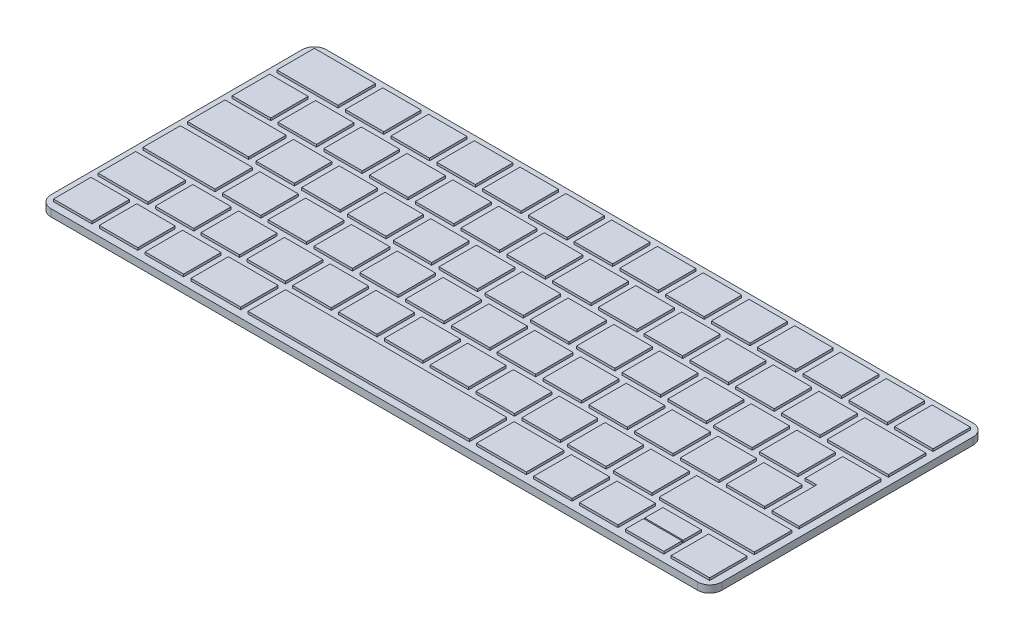
SolidWorks part; units mm, degrees
ref_plane "Front Plane" through (0, 0, 0) normal (0, 0, 1) x (1, 0, 0)
ref_plane "Top Plane" through (0, 0, 0) normal (0, 1, 0) x (1, 0, 0)
ref_plane "Right Plane" through (0, 0, 0) normal (1, 0, 0) x (0, 0, -1)
sketch "Sketch2" plane through (0, 0, 0) normal (1, 0, 0) x (0, 0, -1)
  line L0 (0, 0) -> (-114.5, 0)
  line L1 (-114.5, 0) -> (-114.5, 3)
  line L2 (-114.5, 3) -> (0, 3)
  line L3 (0, 3) -> (0, 0)
  dimension "D2" = 3
  dimension "D3" = 114.5
extrude "Body" add sketch "Sketch2" along normal mid plane 279
sketch "Sketch3" plane through (0, 3, 0) normal (0, 1, 0) x (1, 0, 0)
  line L0 (-139.5, 0) -> (-139.5, -114.5) construction
  line L1 (-136.4455, -111.5) -> (-120.4455, -111.5)
  line L2 (-136.4455, -111.5) -> (-136.4455, -95.9167)
  line L3 (-136.4455, -95.9167) -> (-120.4455, -95.9167)
  line L4 (-120.4455, -111.5) -> (-120.4455, -95.9167)
  line L5 (139.5, -114.5) -> (-139.5, -114.5) construction
  line L6 (-136.4455, -95.9167) -> (-139.5, -95.9167) construction
  line L7 (-117.3909, -111.5) -> (-101.3909, -111.5)
  line L8 (-117.3909, -111.5) -> (-117.3909, -95.9167)
  line L9 (-117.3909, -95.9167) -> (-101.3909, -95.9167)
  line L10 (-101.3909, -111.5) -> (-101.3909, -95.9167)
  line L11 (-98.3364, -111.5) -> (-82.3364, -111.5)
  line L12 (-98.3364, -111.5) -> (-98.3364, -95.9167)
  line L13 (-98.3364, -95.9167) -> (-82.3364, -95.9167)
  line L14 (-82.3364, -111.5) -> (-82.3364, -95.9167)
  line L15 (-79.2818, -111.5) -> (-58.5818, -111.5)
  line L16 (-79.2818, -111.5) -> (-79.2818, -95.9167)
  line L17 (-79.2818, -95.9167) -> (-58.5818, -95.9167)
  line L18 (-58.5818, -111.5) -> (-58.5818, -95.9167)
  line L19 (-55.5273, -111.5) -> (36.4727, -111.5)
  line L20 (-55.5273, -111.5) -> (-55.5273, -95.9167)
  line L21 (-55.5273, -95.9167) -> (36.4727, -95.9167)
  line L22 (36.4727, -111.5) -> (36.4727, -95.9167)
  line L23 (39.5273, -111.5) -> (60.2273, -111.5)
  line L24 (39.5273, -111.5) -> (39.5273, -95.9167)
  line L25 (39.5273, -95.9167) -> (60.2273, -95.9167)
  line L26 (60.2273, -111.5) -> (60.2273, -95.9167)
  line L27 (63.2818, -111.5) -> (79.2818, -111.5)
  line L28 (63.2818, -111.5) -> (63.2818, -95.9167)
  line L29 (63.2818, -95.9167) -> (79.2818, -95.9167)
  line L30 (79.2818, -111.5) -> (79.2818, -95.9167)
  line L31 (82.3364, -111.5) -> (98.3364, -111.5)
  line L32 (82.3364, -111.5) -> (82.3364, -95.9167)
  line L33 (82.3364, -95.9167) -> (98.3364, -95.9167)
  line L34 (98.3364, -111.5) -> (98.3364, -95.9167)
  line L35 (101.3909, -111.5) -> (117.3909, -111.5)
  line L36 (101.3909, -111.5) -> (101.3909, -95.9167)
  line L37 (101.3909, -95.9167) -> (117.3909, -95.9167)
  line L38 (117.3909, -111.5) -> (117.3909, -95.9167)
  line L39 (120.4455, -111.5) -> (136.4455, -111.5)
  line L40 (120.4455, -111.5) -> (120.4455, -95.9167)
  line L41 (120.4455, -95.9167) -> (136.4455, -95.9167)
  line L42 (136.4455, -111.5) -> (136.4455, -95.9167)
  line L43 (-120.4455, -95.9167) -> (-117.3909, -95.9167) construction
  line L44 (-101.3909, -95.9167) -> (-98.3364, -95.9167) construction
  line L45 (-82.3364, -95.9167) -> (-79.2818, -95.9167) construction
  line L46 (-58.5818, -95.9167) -> (-55.5273, -95.9167) construction
  line L47 (36.4727, -95.9167) -> (39.5273, -95.9167) construction
  line L48 (60.2273, -95.9167) -> (63.2818, -95.9167) construction
  line L49 (79.2818, -95.9167) -> (82.3364, -95.9167) construction
  line L50 (136.4455, -95.9167) -> (139.5, -95.9167) construction
  line L51 (98.3364, -95.9167) -> (101.3909, -95.9167) construction
  line L52 (117.3909, -95.9167) -> (120.4455, -95.9167) construction
  line L53 (139.5, 0) -> (139.5, -114.5) construction
  line L54 (-115.7455, -77.3333) -> (-112.6909, -77.3333) construction
  line L55 (-136.4455, -92.9167) -> (-115.7455, -92.9167)
  line L56 (-136.4455, -92.9167) -> (-136.4455, -77.3333)
  line L57 (-136.4455, -77.3333) -> (-115.7455, -77.3333)
  line L58 (-115.7455, -92.9167) -> (-115.7455, -77.3333)
  line L59 (-112.6909, -92.9167) -> (-96.6909, -92.9167)
  line L60 (-112.6909, -92.9167) -> (-112.6909, -77.3333)
  line L61 (-112.6909, -77.3333) -> (-96.6909, -77.3333)
  line L62 (-96.6909, -92.9167) -> (-96.6909, -77.3333)
  line L63 (-93.6364, -92.9167) -> (-77.6364, -92.9167)
  line L64 (-93.6364, -92.9167) -> (-93.6364, -77.3333)
  line L65 (-93.6364, -77.3333) -> (-77.6364, -77.3333)
  line L66 (-77.6364, -92.9167) -> (-77.6364, -77.3333)
  line L67 (-74.5818, -92.9167) -> (-58.5818, -92.9167)
  line L68 (-74.5818, -92.9167) -> (-74.5818, -77.3333)
  line L69 (-74.5818, -77.3333) -> (-58.5818, -77.3333)
  line L70 (-58.5818, -92.9167) -> (-58.5818, -77.3333)
  line L71 (-55.5273, -92.9167) -> (-39.5273, -92.9167)
  line L72 (-55.5273, -92.9167) -> (-55.5273, -77.3333)
  line L73 (-55.5273, -77.3333) -> (-39.5273, -77.3333)
  line L74 (-39.5273, -92.9167) -> (-39.5273, -77.3333)
  line L75 (-36.4727, -92.9167) -> (-20.4727, -92.9167)
  line L76 (-36.4727, -92.9167) -> (-36.4727, -77.3333)
  line L77 (-36.4727, -77.3333) -> (-20.4727, -77.3333)
  line L78 (-20.4727, -92.9167) -> (-20.4727, -77.3333)
  line L79 (-17.4182, -92.9167) -> (-1.4182, -92.9167)
  line L80 (-17.4182, -92.9167) -> (-17.4182, -77.3333)
  line L81 (-17.4182, -77.3333) -> (-1.4182, -77.3333)
  line L82 (-1.4182, -92.9167) -> (-1.4182, -77.3333)
  line L83 (1.6364, -92.9167) -> (17.6364, -92.9167)
  line L84 (1.6364, -92.9167) -> (1.6364, -77.3333)
  line L85 (1.6364, -77.3333) -> (17.6364, -77.3333)
  line L86 (17.6364, -92.9167) -> (17.6364, -77.3333)
  line L87 (20.6909, -92.9167) -> (36.6909, -92.9167)
  line L88 (20.6909, -92.9167) -> (20.6909, -77.3333)
  line L89 (20.6909, -77.3333) -> (36.6909, -77.3333)
  line L90 (36.6909, -92.9167) -> (36.6909, -77.3333)
  line L91 (39.7455, -92.9167) -> (55.7455, -92.9167)
  line L92 (39.7455, -92.9167) -> (39.7455, -77.3333)
  line L93 (39.7455, -77.3333) -> (55.7455, -77.3333)
  line L94 (55.7455, -92.9167) -> (55.7455, -77.3333)
  line L95 (58.8, -92.9167) -> (74.8, -92.9167)
  line L96 (58.8, -92.9167) -> (58.8, -77.3333)
  line L97 (58.8, -77.3333) -> (74.8, -77.3333)
  line L98 (74.8, -92.9167) -> (74.8, -77.3333)
  line L99 (77.8545, -92.9167) -> (93.8545, -92.9167)
  line L100 (77.8545, -92.9167) -> (77.8545, -77.3333)
  line L101 (77.8545, -77.3333) -> (93.8545, -77.3333)
  line L102 (93.8545, -92.9167) -> (93.8545, -77.3333)
  line L103 (-96.6909, -77.3333) -> (-93.6364, -77.3333) construction
  line L104 (-77.6364, -77.3333) -> (-74.5818, -77.3333) construction
  line L105 (-58.5818, -77.3333) -> (-55.5273, -77.3333) construction
  line L106 (-39.5273, -77.3333) -> (-36.4727, -77.3333) construction
  line L107 (-20.4727, -77.3333) -> (-17.4182, -77.3333) construction
  line L108 (-1.4182, -77.3333) -> (1.6364, -77.3333) construction
  line L109 (17.6364, -77.3333) -> (20.6909, -77.3333) construction
  line L110 (36.6909, -77.3333) -> (39.7455, -77.3333) construction
  line L111 (55.7455, -77.3333) -> (58.8, -77.3333) construction
  line L112 (74.8, -77.3333) -> (77.8545, -77.3333) construction
  line L113 (93.8545, -77.3333) -> (96.9091, -77.3333) construction
  line L114 (96.9091, -92.9167) -> (136.4455, -92.9167)
  line L115 (96.9091, -92.9167) -> (96.9091, -77.3333)
  line L116 (96.9091, -77.3333) -> (136.4455, -77.3333)
  line L117 (136.4455, -92.9167) -> (136.4455, -77.3333)
  line L118 (-106.4455, -74.3333) -> (-103.3923, -74.3333) construction
  line L119 (-136.4455, -74.3333) -> (-106.4455, -74.3333)
  line L120 (-136.4455, -74.3333) -> (-136.4455, -58.75)
  line L121 (-136.4455, -58.75) -> (-106.4455, -58.75)
  line L122 (-106.4455, -74.3333) -> (-106.4455, -58.75)
  line L123 (-103.3923, -74.3333) -> (-87.3923, -74.3333)
  line L124 (-103.3923, -74.3333) -> (-103.3923, -58.75)
  line L125 (-103.3923, -58.75) -> (-87.3923, -58.75)
  line L126 (-87.3923, -74.3333) -> (-87.3923, -58.75)
  line L127 (-84.3392, -74.3333) -> (-68.3392, -74.3333)
  line L128 (-84.3392, -74.3333) -> (-84.3392, -58.75)
  line L129 (-84.3392, -58.75) -> (-68.3392, -58.75)
  line L130 (-68.3392, -74.3333) -> (-68.3392, -58.75)
  line L131 (125.2455, -74.3333) -> (136.4455, -74.3333)
  line L132 (125.2455, -74.3333) -> (125.2455, -58.75)
  line L133 (125.2455, -58.75) -> (136.4455, -58.75)
  line L134 (136.4455, -74.3333) -> (136.4455, -58.75)
  line L135 (-65.286, -74.3333) -> (-49.286, -74.3333)
  line L136 (-65.286, -74.3333) -> (-65.286, -58.75)
  line L137 (-65.286, -58.75) -> (-49.286, -58.75)
  line L138 (-49.286, -74.3333) -> (-49.286, -58.75)
  line L139 (-46.2329, -74.3333) -> (-30.2329, -74.3333)
  line L140 (-46.2329, -74.3333) -> (-46.2329, -58.75)
  line L141 (-46.2329, -58.75) -> (-30.2329, -58.75)
  line L142 (-30.2329, -74.3333) -> (-30.2329, -58.75)
  line L143 (-27.1797, -74.3333) -> (-11.1797, -74.3333)
  line L144 (-27.1797, -74.3333) -> (-27.1797, -58.75)
  line L145 (-27.1797, -58.75) -> (-11.1797, -58.75)
  line L146 (-11.1797, -74.3333) -> (-11.1797, -58.75)
  line L147 (-8.1266, -74.3333) -> (7.8734, -74.3333)
  line L148 (-8.1266, -74.3333) -> (-8.1266, -58.75)
  line L149 (-8.1266, -58.75) -> (7.8734, -58.75)
  line L150 (7.8734, -74.3333) -> (7.8734, -58.75)
  line L151 (10.9266, -74.3333) -> (26.9266, -74.3333)
  line L152 (10.9266, -74.3333) -> (10.9266, -58.75)
  line L153 (10.9266, -58.75) -> (26.9266, -58.75)
  line L154 (26.9266, -74.3333) -> (26.9266, -58.75)
  line L155 (45.9797, -74.3333) -> (29.9797, -74.3333)
  line L156 (45.9797, -74.3333) -> (45.9797, -58.75)
  line L157 (45.9797, -58.75) -> (29.9797, -58.75)
  line L158 (29.9797, -74.3333) -> (29.9797, -58.75)
  line L159 (49.0329, -58.75) -> (65.0329, -58.75)
  line L160 (49.0329, -58.75) -> (49.0329, -74.3333)
  line L161 (49.0329, -74.3333) -> (65.0329, -74.3333)
  line L162 (65.0329, -58.75) -> (65.0329, -74.3333)
  line L163 (68.086, -74.3333) -> (84.086, -74.3333)
  line L164 (68.086, -74.3333) -> (68.086, -58.75)
  line L165 (68.086, -58.75) -> (84.086, -58.75)
  line L166 (84.086, -74.3333) -> (84.086, -58.75)
  line L167 (87.1392, -74.3333) -> (103.1392, -74.3333)
  line L168 (87.1392, -74.3333) -> (87.1392, -58.75)
  line L169 (87.1392, -58.75) -> (103.1392, -58.75)
  line L170 (103.1392, -74.3333) -> (103.1392, -58.75)
  line L171 (-87.3923, -74.3333) -> (-84.3392, -74.3333) construction
  line L172 (-68.3392, -74.3333) -> (-65.286, -74.3333) construction
  line L173 (-49.286, -74.3333) -> (-46.2329, -74.3333) construction
  line L174 (-30.2329, -74.3333) -> (-27.1797, -74.3333) construction
  line L175 (-11.1797, -74.3333) -> (-8.1266, -74.3333) construction
  line L176 (7.8734, -74.3333) -> (10.9266, -74.3333) construction
  line L177 (26.9266, -74.3333) -> (29.9797, -74.3333) construction
  line L178 (45.9797, -74.3333) -> (49.0329, -74.3333) construction
  line L179 (65.0329, -74.3333) -> (68.086, -74.3333) construction
  line L180 (84.086, -74.3333) -> (87.1392, -74.3333) construction
  line L181 (103.1392, -74.3333) -> (106.1923, -74.3333) construction
  line L182 (106.1923, -74.3333) -> (122.1923, -74.3333)
  line L183 (106.1923, -74.3333) -> (106.1923, -58.75)
  line L184 (106.1923, -58.75) -> (122.1923, -58.75)
  line L185 (122.1923, -74.3333) -> (122.1923, -58.75)
  line L186 (122.1923, -74.3333) -> (125.2455, -74.3333) construction
  line L187 (-120.4455, -21.5833) -> (-117.4077, -21.5833) construction
  line L188 (-136.4455, -37.1667) -> (-120.4455, -37.1667)
  line L189 (-136.4455, -37.1667) -> (-136.4455, -21.5833)
  line L190 (-136.4455, -21.5833) -> (-120.4455, -21.5833)
  line L191 (-120.4455, -37.1667) -> (-120.4455, -21.5833)
  line L192 (-117.4077, -37.1667) -> (-101.4077, -37.1667)
  line L193 (-117.4077, -37.1667) -> (-117.4077, -21.5833)
  line L194 (-117.4077, -21.5833) -> (-101.4077, -21.5833)
  line L195 (-101.4077, -37.1667) -> (-101.4077, -21.5833)
  line L196 (-98.3699, -37.1667) -> (-82.3699, -37.1667)
  line L197 (-98.3699, -37.1667) -> (-98.3699, -21.5833)
  line L198 (-98.3699, -21.5833) -> (-82.3699, -21.5833)
  line L199 (-82.3699, -37.1667) -> (-82.3699, -21.5833)
  line L200 (-79.3322, -37.1667) -> (-63.3322, -37.1667)
  line L201 (-79.3322, -37.1667) -> (-79.3322, -21.5833)
  line L202 (-79.3322, -21.5833) -> (-63.3322, -21.5833)
  line L203 (-63.3322, -37.1667) -> (-63.3322, -21.5833)
  line L204 (-60.2944, -37.1667) -> (-44.2944, -37.1667)
  line L205 (-60.2944, -37.1667) -> (-60.2944, -21.5833)
  line L206 (-60.2944, -21.5833) -> (-44.2944, -21.5833)
  line L207 (-44.2944, -37.1667) -> (-44.2944, -21.5833)
  line L208 (-41.2566, -37.1667) -> (-25.2566, -37.1667)
  line L209 (-41.2566, -37.1667) -> (-41.2566, -21.5833)
  line L210 (-41.2566, -21.5833) -> (-25.2566, -21.5833)
  line L211 (-25.2566, -37.1667) -> (-25.2566, -21.5833)
  line L212 (-22.2189, -21.5833) -> (-6.2189, -21.5833)
  line L213 (-22.2189, -21.5833) -> (-22.2189, -37.1667)
  line L214 (-22.2189, -37.1667) -> (-6.2189, -37.1667)
  line L215 (-6.2189, -21.5833) -> (-6.2189, -37.1667)
  line L216 (-3.1811, -37.1667) -> (12.8189, -37.1667)
  line L217 (-3.1811, -37.1667) -> (-3.1811, -21.5833)
  line L218 (-3.1811, -21.5833) -> (12.8189, -21.5833)
  line L219 (12.8189, -37.1667) -> (12.8189, -21.5833)
  line L220 (15.8566, -37.1667) -> (31.8566, -37.1667)
  line L221 (15.8566, -37.1667) -> (15.8566, -21.5833)
  line L222 (15.8566, -21.5833) -> (31.8566, -21.5833)
  line L223 (31.8566, -37.1667) -> (31.8566, -21.5833)
  line L224 (34.8944, -37.1667) -> (50.8944, -37.1667)
  line L225 (34.8944, -37.1667) -> (34.8944, -21.5833)
  line L226 (34.8944, -21.5833) -> (50.8944, -21.5833)
  line L227 (50.8944, -37.1667) -> (50.8944, -21.5833)
  line L228 (53.9322, -37.1667) -> (69.9322, -37.1667)
  line L229 (53.9322, -37.1667) -> (53.9322, -21.5833)
  line L230 (53.9322, -21.5833) -> (69.9322, -21.5833)
  line L231 (69.9322, -37.1667) -> (69.9322, -21.5833)
  line L232 (88.9699, -21.5833) -> (72.9699, -21.5833)
  line L233 (88.9699, -21.5833) -> (88.9699, -37.1667)
  line L234 (88.9699, -37.1667) -> (72.9699, -37.1667)
  line L235 (72.9699, -21.5833) -> (72.9699, -37.1667)
  line L236 (108.0077, -37.1667) -> (92.0077, -37.1667)
  line L237 (108.0077, -37.1667) -> (108.0077, -21.5833)
  line L238 (108.0077, -21.5833) -> (92.0077, -21.5833)
  line L239 (92.0077, -37.1667) -> (92.0077, -21.5833)
  line L240 (-101.4077, -21.5833) -> (-98.3699, -21.5833) construction
  line L241 (88.9699, -21.5833) -> (92.0077, -21.5833) construction
  line L242 (-82.3699, -21.5833) -> (-79.3322, -21.5833) construction
  line L243 (-63.3322, -21.5833) -> (-60.2944, -21.5833) construction
  line L244 (-44.2944, -21.5833) -> (-41.2566, -21.5833) construction
  line L245 (108.0077, -21.5833) -> (111.0455, -21.5833) construction
  line L246 (-25.2566, -21.5833) -> (-22.2189, -21.5833) construction
  line L247 (-6.2189, -21.5833) -> (-3.1811, -21.5833) construction
  line L248 (12.8189, -21.5833) -> (15.8566, -21.5833) construction
  line L249 (31.8566, -21.5833) -> (34.8944, -21.5833) construction
  line L250 (50.8944, -21.5833) -> (53.9322, -21.5833) construction
  line L251 (69.9322, -21.5833) -> (72.9699, -21.5833) construction
  line L252 (-136.4455, -58.75) -> (-136.4455, -55.75) construction
  line L253 (-136.4455, -55.75) -> (-136.4455, -40.1667) construction
  line L254 (111.0455, -37.1667) -> (136.4455, -37.1667)
  line L255 (111.0455, -37.1667) -> (111.0455, -21.5833)
  line L256 (111.0455, -21.5833) -> (136.4455, -21.5833)
  line L257 (136.4455, -37.1667) -> (136.4455, -21.5833)
  line L258 (-136.4455, -40.1667) -> (-136.4455, -37.1667) construction
  line L259 (-136.4455, -111.5) -> (-136.4455, -114.5) construction
  line L260 (-136.4455, -92.9167) -> (-136.4455, -95.9167) construction
  line L261 (-136.4455, -74.3333) -> (-136.4455, -77.3333) construction
  line L262 (-136.4455, -77.3333) -> (-136.3345, -77.3915) construction
  line L263 (-136.4455, -21.5833) -> (-136.4455, -18.5833) construction
  line L264 (-136.4455, -18.5833) -> (-136.4455, -3) construction
  line L265 (-136.4455, -3) -> (-136.4455, 0) construction
  line L266 (139.5, 0) -> (-139.5, 0) construction
  dimension "D1" = 30
  dimension "D2" = 3
  dimension "D3" = 16
  dimension "D4" = 11.2
  dimension "D5" = 20.7
  dimension "D6" = 92
  dimension "D7" = 25.4
extrude "Keys A" add sketch "Sketch3" along normal blind 1
sketch "Sketch4" plane through (0, 3, 0) normal (0, 1, 0) x (1, 0, 0)
  line L1 (-136.4455, -55.75) -> (-111.0455, -55.75)
  line L2 (-136.4455, -55.75) -> (-136.4455, -40.1667)
  line L3 (-136.4455, -40.1667) -> (-111.0455, -40.1667)
  line L4 (-111.0455, -55.75) -> (-111.0455, -40.1667)
  line L5 (-107.9923, -55.75) -> (-92.0077, -55.75)
  line L6 (-107.9923, -55.75) -> (-107.9923, -40.1667)
  line L7 (-107.9923, -40.1667) -> (-92.0077, -40.1667)
  line L8 (-92.0077, -55.75) -> (-92.0077, -40.1667)
  line L9 (-88.9545, -55.75) -> (-72.9699, -55.75)
  line L10 (-88.9545, -55.75) -> (-88.9545, -40.1667)
  line L11 (-88.9545, -40.1667) -> (-72.9699, -40.1667)
  line L12 (-72.9699, -55.75) -> (-72.9699, -40.1667)
  line L13 (-69.9168, -55.75) -> (-53.9322, -55.75)
  line L14 (-69.9168, -55.75) -> (-69.9168, -40.1667)
  line L15 (-69.9168, -40.1667) -> (-53.9322, -40.1667)
  line L16 (-53.9322, -55.75) -> (-53.9322, -40.1667)
  line L17 (-50.879, -55.75) -> (-34.8944, -55.75)
  line L18 (-50.879, -55.75) -> (-50.879, -40.1667)
  line L19 (-50.879, -40.1667) -> (-34.8944, -40.1667)
  line L20 (-34.8944, -55.75) -> (-34.8944, -40.1667)
  line L21 (-31.8413, -55.75) -> (-15.8566, -55.75)
  line L22 (-31.8413, -55.75) -> (-31.8413, -40.1667)
  line L23 (-31.8413, -40.1667) -> (-15.8566, -40.1667)
  line L24 (-15.8566, -55.75) -> (-15.8566, -40.1667)
  line L25 (-12.8035, -55.75) -> (3.1811, -55.75)
  line L26 (-12.8035, -55.75) -> (-12.8035, -40.1667)
  line L27 (-12.8035, -40.1667) -> (3.1811, -40.1667)
  line L28 (3.1811, -55.75) -> (3.1811, -40.1667)
  line L29 (6.2343, -55.75) -> (22.2189, -55.75)
  line L30 (6.2343, -55.75) -> (6.2343, -40.1667)
  line L31 (6.2343, -40.1667) -> (22.2189, -40.1667)
  line L32 (22.2189, -55.75) -> (22.2189, -40.1667)
  line L33 (25.272, -55.75) -> (41.2566, -55.75)
  line L34 (25.272, -55.75) -> (25.272, -40.1667)
  line L35 (25.272, -40.1667) -> (41.2566, -40.1667)
  line L36 (41.2566, -55.75) -> (41.2566, -40.1667)
  line L37 (44.3098, -55.75) -> (60.2944, -55.75)
  line L38 (44.3098, -55.75) -> (44.3098, -40.1667)
  line L39 (44.3098, -40.1667) -> (60.2944, -40.1667)
  line L40 (60.2944, -55.75) -> (60.2944, -40.1667)
  line L41 (63.3476, -55.75) -> (79.3322, -55.75)
  line L42 (63.3476, -55.75) -> (63.3476, -40.1667)
  line L43 (63.3476, -40.1667) -> (79.3322, -40.1667)
  line L44 (79.3322, -55.75) -> (79.3322, -40.1667)
  line L45 (-111.0455, -40.1667) -> (-107.9923, -40.1667) construction
  line L46 (-92.0077, -40.1667) -> (-88.9545, -40.1667) construction
  line L47 (-72.9699, -40.1667) -> (-69.9168, -40.1667) construction
  line L48 (-53.9322, -40.1667) -> (-50.879, -40.1667) construction
  line L49 (82.3853, -55.75) -> (98.3699, -55.75)
  line L50 (82.3853, -55.75) -> (82.3853, -40.1667)
  line L51 (82.3853, -40.1667) -> (98.3699, -40.1667)
  line L52 (98.3699, -55.75) -> (98.3699, -40.1667)
  line L53 (101.4231, -55.75) -> (117.4077, -55.75)
  line L54 (101.4231, -55.75) -> (101.4231, -40.1667)
  line L55 (101.4231, -40.1667) -> (117.4077, -40.1667)
  line L56 (117.4077, -55.75) -> (117.4077, -40.1667)
  line L61 (-34.8944, -40.1667) -> (-31.8413, -40.1667) construction
  line L62 (-15.8566, -40.1667) -> (-12.8035, -40.1667) construction
  line L63 (-136.4455, -58.75) -> (-136.4455, -74.3333) construction
  line L64 (3.1811, -40.1667) -> (6.2343, -40.1667) construction
  line L65 (22.2189, -40.1667) -> (25.272, -40.1667) construction
  line L66 (-136.4455, -37.1667) -> (-136.4455, -40.1667) construction
  line L67 (41.2566, -40.1667) -> (44.3098, -40.1667) construction
  line L68 (60.2944, -40.1667) -> (63.3476, -40.1667) construction
  line L69 (79.3322, -40.1667) -> (82.3853, -40.1667) construction
  line L70 (98.3699, -40.1667) -> (101.4231, -40.1667) construction
  line L71 (-136.4455, -55.75) -> (-136.4455, -58.75) construction
  line L72 (111.0455, -37.1667) -> (136.4455, -37.1667) construction
  line L73 (-106.4455, -74.3333) -> (-103.3923, -74.3333) construction
  line L74 (-136.4455, -74.3333) -> (-136.4455, -77.3333) construction
  line L76 (-136.4455, -18.5833) -> (-111.0455, -18.5833)
  line L77 (-136.4455, -18.5833) -> (-136.4455, -3)
  line L78 (-136.4455, -3) -> (-111.0455, -3)
  line L79 (-111.0455, -18.5833) -> (-111.0455, -3)
  line L80 (136.4455, -74.3333) -> (136.4455, -58.75) construction
  line L81 (-107.9923, -18.5833) -> (-92.0077, -18.5833)
  line L82 (-107.9923, -18.5833) -> (-107.9923, -3)
  line L83 (-107.9923, -3) -> (-92.0077, -3)
  line L84 (-92.0077, -18.5833) -> (-92.0077, -3)
  line L85 (-88.9545, -18.5833) -> (-72.9699, -18.5833)
  line L86 (-88.9545, -18.5833) -> (-88.9545, -3)
  line L87 (-88.9545, -3) -> (-72.9699, -3)
  line L88 (-72.9699, -18.5833) -> (-72.9699, -3)
  line L89 (-69.9168, -18.5833) -> (-53.9322, -18.5833)
  line L90 (-69.9168, -18.5833) -> (-69.9168, -3)
  line L91 (-69.9168, -3) -> (-53.9322, -3)
  line L92 (-53.9322, -18.5833) -> (-53.9322, -3)
  line L93 (-50.879, -18.5833) -> (-34.8944, -18.5833)
  line L94 (-50.879, -18.5833) -> (-50.879, -3)
  line L95 (-50.879, -3) -> (-34.8944, -3)
  line L96 (-34.8944, -18.5833) -> (-34.8944, -3)
  line L97 (-31.8413, -18.5833) -> (-15.8566, -18.5833)
  line L98 (-31.8413, -18.5833) -> (-31.8413, -3)
  line L99 (-31.8413, -3) -> (-15.8566, -3)
  line L100 (-15.8566, -18.5833) -> (-15.8566, -3)
  line L101 (-12.8035, -18.5833) -> (3.1811, -18.5833)
  line L102 (-12.8035, -18.5833) -> (-12.8035, -3)
  line L103 (-12.8035, -3) -> (3.1811, -3)
  line L104 (3.1811, -18.5833) -> (3.1811, -3)
  line L105 (6.2343, -18.5833) -> (22.2189, -18.5833)
  line L106 (6.2343, -18.5833) -> (6.2343, -3)
  line L107 (6.2343, -3) -> (22.2189, -3)
  line L108 (22.2189, -18.5833) -> (22.2189, -3)
  line L109 (120.4608, -55.75) -> (136.4455, -55.75)
  line L110 (120.4608, -55.75) -> (120.4608, -40.1667)
  line L111 (120.4608, -40.1667) -> (136.4455, -40.1667)
  line L112 (136.4455, -55.75) -> (136.4455, -40.1667)
  line L113 (117.4077, -40.1667) -> (120.4608, -40.1667) construction
  line L115 (25.272, -18.5833) -> (41.2566, -18.5833)
  line L116 (25.272, -18.5833) -> (25.272, -3)
  line L117 (25.272, -3) -> (41.2566, -3)
  line L118 (41.2566, -18.5833) -> (41.2566, -3)
  line L119 (44.3098, -18.5833) -> (60.2944, -18.5833)
  line L120 (44.3098, -18.5833) -> (44.3098, -3)
  line L121 (44.3098, -3) -> (60.2944, -3)
  line L122 (60.2944, -18.5833) -> (60.2944, -3)
  line L123 (63.3476, -18.5833) -> (79.3322, -18.5833)
  line L124 (63.3476, -18.5833) -> (63.3476, -3)
  line L125 (63.3476, -3) -> (79.3322, -3)
  line L126 (79.3322, -18.5833) -> (79.3322, -3)
  line L127 (82.3853, -18.5833) -> (98.3699, -18.5833)
  line L128 (82.3853, -18.5833) -> (82.3853, -3)
  line L129 (82.3853, -3) -> (98.3699, -3)
  line L130 (98.3699, -18.5833) -> (98.3699, -3)
  line L131 (101.4231, -18.5833) -> (117.4077, -18.5833)
  line L132 (101.4231, -18.5833) -> (101.4231, -3)
  line L133 (101.4231, -3) -> (117.4077, -3)
  line L134 (117.4077, -18.5833) -> (117.4077, -3)
  line L135 (120.4608, -18.5833) -> (136.4455, -18.5833)
  line L136 (120.4608, -18.5833) -> (120.4608, -3)
  line L137 (120.4608, -3) -> (136.4455, -3)
  line L138 (136.4455, -18.5833) -> (136.4455, -3)
extrude "Keys B" add sketch "Sketch4" along normal up to surface (1 mm away) up to face at (-128.4455, 4, 29.375)
sketch "Sketch5" plane through (0, 4, 0) normal (0, 1, 0) x (1, 0, 0)
  line L1 (136.4455, -55.75) -> (125.2455, -55.75)
  line L2 (136.4455, -55.75) -> (136.4455, -58.75)
  line L3 (136.4455, -58.75) -> (125.2455, -58.75)
  line L4 (125.2455, -55.75) -> (125.2455, -58.75)
extrude "Key Enter" add sketch "Sketch5" against normal up to next
sketch "Sketch6" plane through (0, 4, 0) normal (0, 1, 0) x (1, 0, 0)
  line L0 (101.3909, -95.9167) -> (101.3909, -111.5) construction
  line L1 (101.3909, -103.9583) -> (117.3909, -103.9583)
  line L2 (101.3909, -103.9583) -> (101.3909, -103.4583)
  line L3 (101.3909, -103.4583) -> (117.3909, -103.4583)
  line L4 (117.3909, -103.9583) -> (117.3909, -103.4583)
  line L5 (101.3909, -103.9583) -> (117.3909, -103.4583) construction
  line L6 (101.3909, -103.4583) -> (117.3909, -103.9583) construction
  line L7 (117.3909, -111.5) -> (117.3909, -95.9167) construction
  line L8 (101.3909, -103.7083) -> (109.3909, -103.7083) construction
  line L9 (101.3909, -95.9167) -> (101.3909, -111.5) construction
  point P0 (109.3909, -103.7083)
  dimension "D1" = 0.5
extrude "Slit" cut sketch "Sketch6" against normal up to surface (1 mm away) up to face at (109.4154, 3, 10.7917)
fillet "Corner" radius 5 4 edges at (139.5, 1.5, 0) (139.5, 1.5, 114.5) (-139.5, 1.5, 0) (-139.5, 1.5, 114.5)
